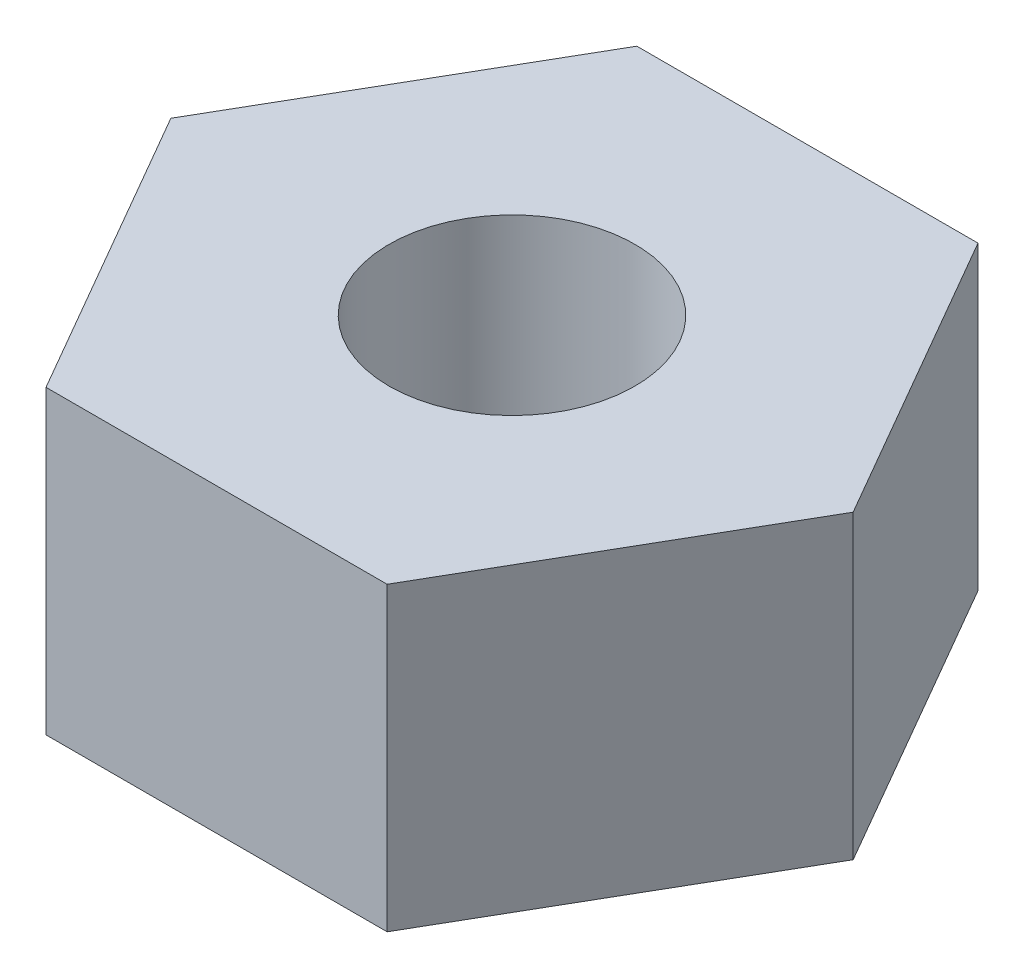
SolidWorks part; units mm, degrees
ref_plane "Front Plane" through (0, 0, 0) normal (0, 0, 1) x (1, 0, 0)
ref_plane "Top Plane" through (0, 0, 0) normal (0, 1, 0) x (1, 0, 0)
ref_plane "Right Plane" through (0, 0, 0) normal (1, 0, 0) x (0, 0, -1)
sketch "Sketch1" plane through (0, 0, 0) normal (0, 1, 0) x (1, 0, 0)
  line L1 (6.8, 0) -> (3.4, 5.889)
  line L2 (3.4, 5.889) -> (-3.4, 5.889)
  line L3 (-3.4, 5.889) -> (-6.8, 0)
  line L4 (-6.8, 0) -> (-3.4, -5.889)
  line L5 (-3.4, -5.889) -> (3.4, -5.889)
  line L6 (3.4, -5.889) -> (6.8, 0)
  circle A0 centre (0, 0) radius 6.8
  circle A1 centre (0, 0) radius 2.45
  circle A2 centre (0, 0) radius 5.889 construction
  dimension "D1" = 13.6
  dimension "D2" = 4.9
  dimension "D3" = 13.6
extrude "Boss-Extrude1" add sketch "Sketch1" along normal blind 6 contours L5 L6 L1 L2 L3 L4 A1
